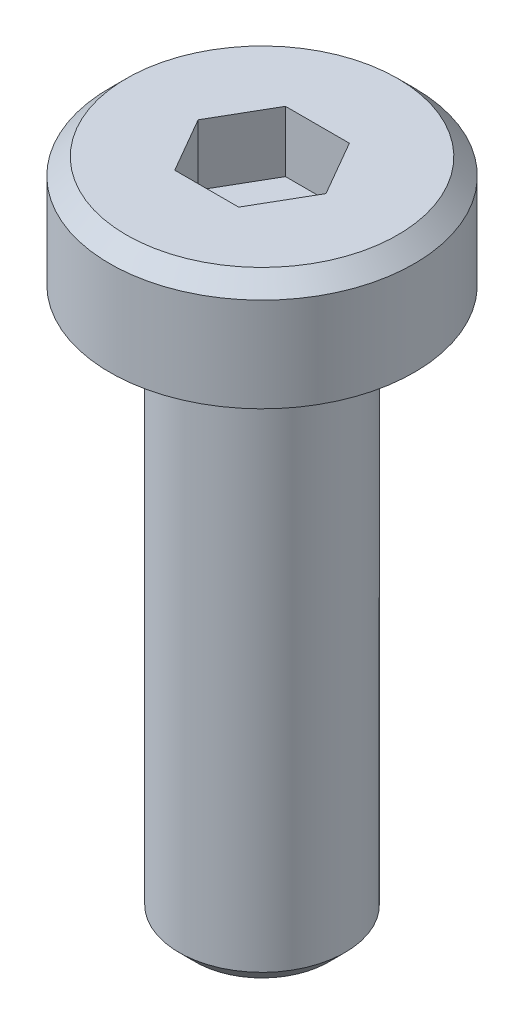
SolidWorks part; units mm, degrees
ref_plane "前视基准面" through (0, 0, 0) normal (0, 0, 1) x (1, 0, 0)
ref_plane "上视基准面" through (0, 0, 0) normal (0, 1, 0) x (1, 0, 0)
ref_plane "右视基准面" through (0, 0, 0) normal (1, 0, 0) x (0, 0, -1)
other "Configuration Table"
sketch "轴向轮廓" plane through (0, 0, 0) normal (0, 0, 1) x (1, 0, 0)
  line L0 (0, -10) -> (1.2, -10)
  line L1 (1.2, -10) -> (1.5, -9.7)
  line L2 (1.5, -9.7) -> (1.5, 0)
  line L3 (1.5, 0) -> (2.75, 0)
  line L4 (2.75, 0) -> (2.75, 1.7)
  line L5 (2.75, 1.7) -> (2.45, 2)
  line L6 (2.45, 2) -> (0, 2)
  line L7 (0, 2) -> (0, -10)
  line L8 (0, -12) -> (0, 4) construction
revolve "螺钉外形_旋转" add sketch "轴向轮廓" angle 360 about L8
sketch "内六角轮廓" plane through (0, 2, 0) normal (0, 1, 0) x (1, 0, 0)
  line L0 (1.1547, 0) -> (0.5774, 1)
  line L1 (0.5774, 1) -> (-0.5774, 1)
  line L2 (-0.5774, 1) -> (-1.1547, 0)
  line L3 (-1.1547, 0) -> (-0.5774, -1)
  line L4 (-0.5774, -1) -> (0.5774, -1)
  line L5 (0.5774, -1) -> (1.1547, 0)
extrude "内六角" cut sketch "内六角轮廓" against normal blind 1.1
